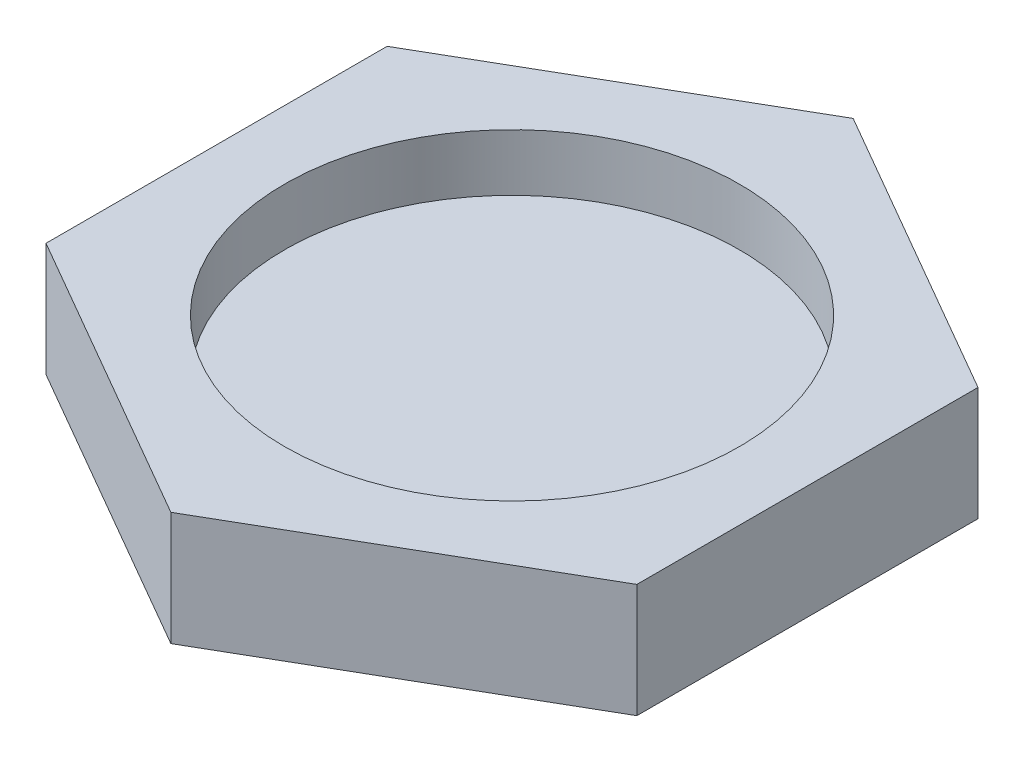
SolidWorks part; units mm, degrees
ref_plane "Front Plane" through (0, 0, 0) normal (0, 0, 1) x (1, 0, 0)
ref_plane "Top Plane" through (0, 0, 0) normal (0, 1, 0) x (1, 0, 0)
ref_plane "Right Plane" through (0, 0, 0) normal (1, 0, 0) x (0, 0, -1)
sketch "Sketch1" plane through (0, 0, 0) normal (0, 1, 0) x (1, 0, 0)
  line L0 (0, 152.4) -> (-131.9823, 76.2)
  line L1 (-131.9823, 76.2) -> (-131.9823, -76.2)
  line L2 (-131.9823, -76.2) -> (0, -152.4)
  line L3 (0, -152.4) -> (131.9823, -76.2)
  line L4 (131.9823, -76.2) -> (131.9823, 76.2)
  line L5 (131.9823, 76.2) -> (0, 152.4)
  circle A1 centre (0, 0) radius 101.6 construction
  point P7 (-65.9911, 114.3)
  dimension "D2" = 203.2
extrude "Boss-Extrude1" add sketch "Sketch1" along normal blind 50.8
sketch "Sketch2" plane through (0, 50.8, 0) normal (0, 1, 0) x (1, 0, 0)
  circle A0 centre (0, 0) radius 101.6
extrude "Cut-Extrude1" cut sketch "Sketch2" against normal blind 25.4
